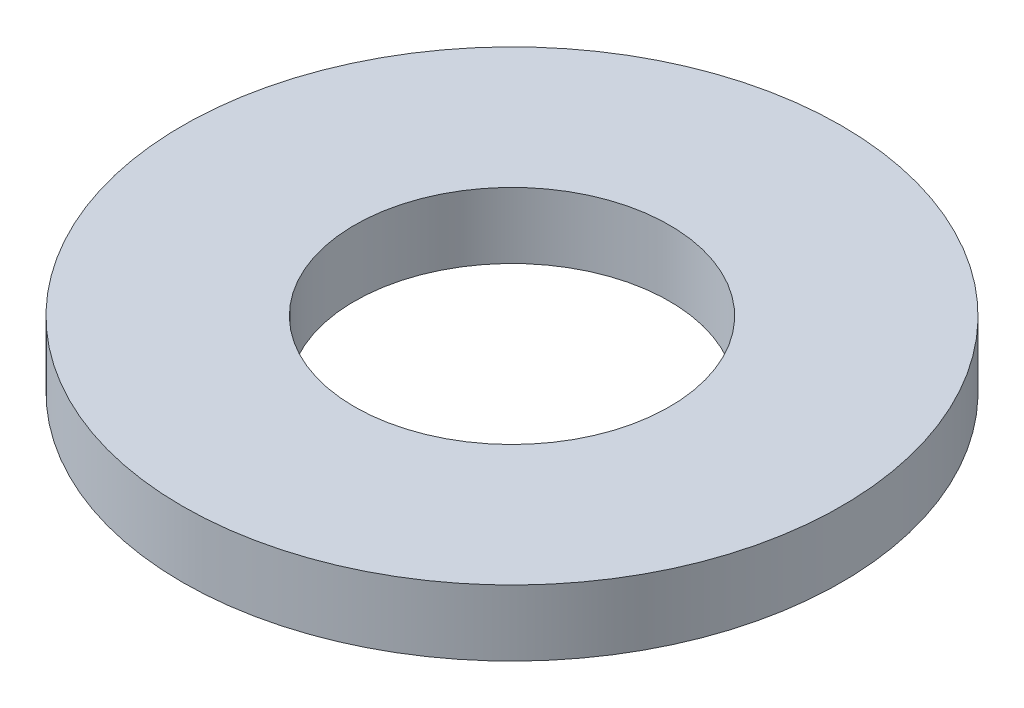
SolidWorks part; units mm, degrees
ref_plane "Front Plane" through (0, 0, 0) normal (0, 0, 1) x (1, 0, 0)
ref_plane "Top Plane" through (0, 0, 0) normal (0, 1, 0) x (1, 0, 0)
ref_plane "Right Plane" through (0, 0, 0) normal (1, 0, 0) x (0, 0, -1)
sketch "Sketch1" plane through (0, 0, 0) normal (0, 1, 0) x (1, 0, 0)
  circle A0 centre (0, 0) radius 2.15
  circle A1 centre (0, 0) radius 4.5
  dimension "D1" = 4.3
  dimension "D2" = 9
extrude "Boss-Extrude1" add sketch "Sketch1" along normal blind 0.9
